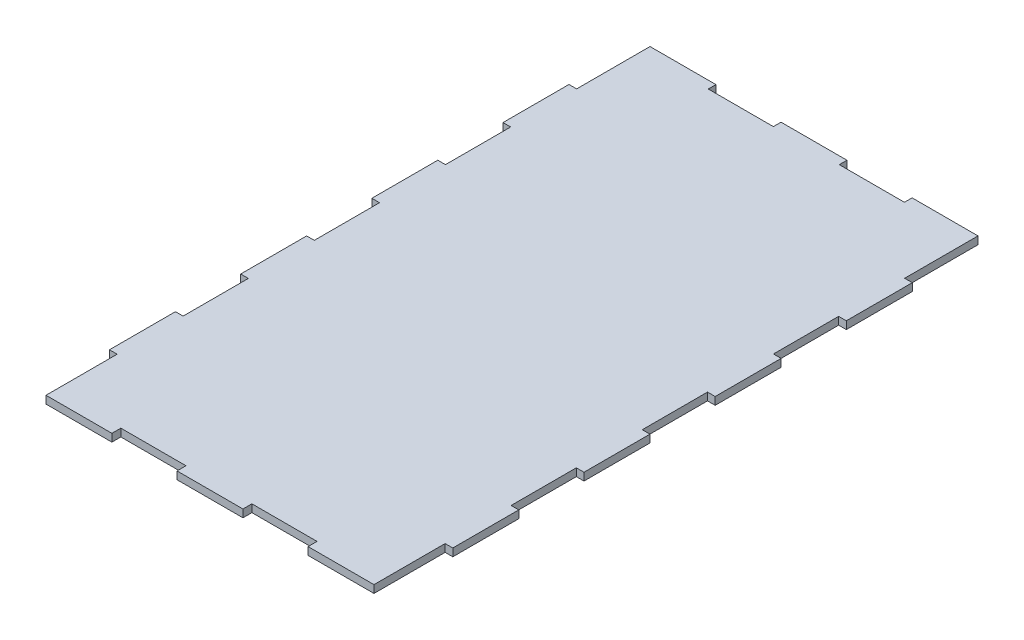
SolidWorks part; units mm, degrees
ref_plane "Front Plane" through (0, 0, 0) normal (0, 0, 1) x (1, 0, 0)
ref_plane "Top Plane" through (0, 0, 0) normal (0, 1, 0) x (1, 0, 0)
ref_plane "Right Plane" through (0, 0, 0) normal (1, 0, 0) x (0, 0, -1)
sketch "Sketch1" plane through (0, 0, 0) normal (0, 1, 0) x (1, 0, 0)
  line L0 (-64.15, 204.08) -> (-64.15, 230.66)
  line L1 (-64.15, 204.08) -> (-67.15, 204.08)
  line L2 (-67.15, 204.08) -> (-67.15, 178.2737)
  line L3 (-67.15, 178.2737) -> (-64.15, 178.2737)
  line L4 (-67.15, 126.9612) -> (-67.15, 152.7675)
  line L5 (-67.15, 152.7675) -> (-64.15, 152.7675)
  line L6 (-64.15, 152.7675) -> (-64.15, 178.2737)
  line L7 (-67.15, 126.9612) -> (-64.15, 126.9612)
  line L8 (-64.15, 126.9612) -> (-64.15, 101.455)
  line L9 (-64.15, 101.455) -> (-67.15, 101.455)
  line L10 (-67.15, 101.455) -> (-67.15, 75.6488)
  line L11 (-67.15, 75.6488) -> (-64.15, 75.6488)
  line L12 (-64.15, 75.6488) -> (-64.15, 50.1425)
  line L13 (-64.15, 50.1425) -> (-67.15, 50.1425)
  line L14 (-67.15, 50.1425) -> (-67.15, 24.3363)
  line L15 (-67.15, 24.3363) -> (-64.15, 24.3362)
  line L16 (-64.15, 24.3362) -> (-64.15, -1.17)
  line L17 (-64.15, 232.78) -> (-38.37, 232.78)
  line L18 (-38.37, 232.78) -> (-38.37, 229.78)
  line L19 (-38.37, 229.78) -> (-12.89, 229.78)
  line L20 (-12.89, 229.78) -> (-12.89, 232.78)
  line L21 (-64.15, 204.08) -> (-64.15, 178.5737) construction
  line L22 (-64.15, 178.5737) -> (-64.15, 178.2737) construction
  line L23 (-12.89, 232.78) -> (12.89, 232.78)
  line L24 (-38.37, 229.78) -> (-63.85, 229.78) construction
  line L25 (-63.85, 229.78) -> (-64.15, 229.78) construction
  line L26 (0, 4.2146) -> (0, 0) construction
  line L27 (-64.15, 230.66) -> (-64.15, 232.78)
  line L28 (-64.15, -1.17) -> (-64.15, -3.5)
  line L29 (63.85, 229.78) -> (64.15, 229.78) construction
  line L30 (38.37, 229.78) -> (63.85, 229.78) construction
  line L31 (64.15, 178.5737) -> (64.15, 178.2738) construction
  line L32 (64.15, 204.08) -> (64.15, 178.5737) construction
  line L33 (64.15, -1.17) -> (64.15, -3.5)
  line L34 (64.15, 230.66) -> (64.15, 232.78)
  line L35 (12.89, 229.78) -> (12.89, 232.78)
  line L36 (38.37, 229.78) -> (12.89, 229.78)
  line L37 (38.37, 232.78) -> (38.37, 229.78)
  line L38 (64.15, 232.78) -> (38.37, 232.78)
  line L39 (64.15, 24.3363) -> (64.15, -1.17)
  line L40 (67.15, 24.3363) -> (64.15, 24.3363)
  line L41 (67.15, 50.1425) -> (67.15, 24.3363)
  line L42 (64.15, 50.1425) -> (67.15, 50.1425)
  line L43 (64.15, 75.6488) -> (64.15, 50.1425)
  line L44 (67.15, 75.6488) -> (64.15, 75.6488)
  line L45 (67.15, 101.455) -> (67.15, 75.6488)
  line L46 (64.15, 101.455) -> (67.15, 101.455)
  line L47 (64.15, 126.9612) -> (64.15, 101.455)
  line L48 (67.15, 126.9612) -> (64.15, 126.9612)
  line L49 (64.15, 152.7675) -> (64.15, 178.2738)
  line L50 (67.15, 152.7675) -> (64.15, 152.7675)
  line L51 (67.15, 126.9612) -> (67.15, 152.7675)
  line L52 (67.15, 178.2738) -> (64.15, 178.2738)
  line L53 (67.15, 204.08) -> (67.15, 178.2738)
  line L54 (64.15, 204.08) -> (67.15, 204.08)
  line L55 (64.15, 204.08) -> (64.15, 230.66)
  line L56 (64.15, -3.5) -> (38.37, -3.5)
  line L57 (38.37, -3.5) -> (38.37, 0)
  line L58 (38.37, 0) -> (12.89, 0)
  line L59 (12.89, 0) -> (12.89, -3.5)
  line L60 (12.89, -3.5) -> (-12.89, -3.5)
  line L61 (-12.89, -3.5) -> (-12.89, 0)
  line L62 (-12.89, 0) -> (-38.37, 0)
  line L63 (-38.37, 0) -> (-38.37, -3.5)
  line L64 (-38.37, -3.5) -> (-64.15, -3.5)
  line L65 (-12.89, 0) -> (12.59, 0) construction
  line L66 (12.59, 0) -> (12.89, 0) construction
  point P26 (0, 232.78)
  point P60 (38.37, -9.1063)
  point P68 (38.37, 255.531)
  point P69 (0, 0)
  dimension "D1" = 0.3
  dimension "D2" = 236.28
  dimension "D3" = 2.12
  dimension "D4" = 26.58
  dimension "D5" = 3
  dimension "D6" = 64.15
  dimension "D7" = 2.33
  dimension "D8" = 3.5
extrude "Boss-Extrude1" add sketch "Sketch1" along normal blind 3
